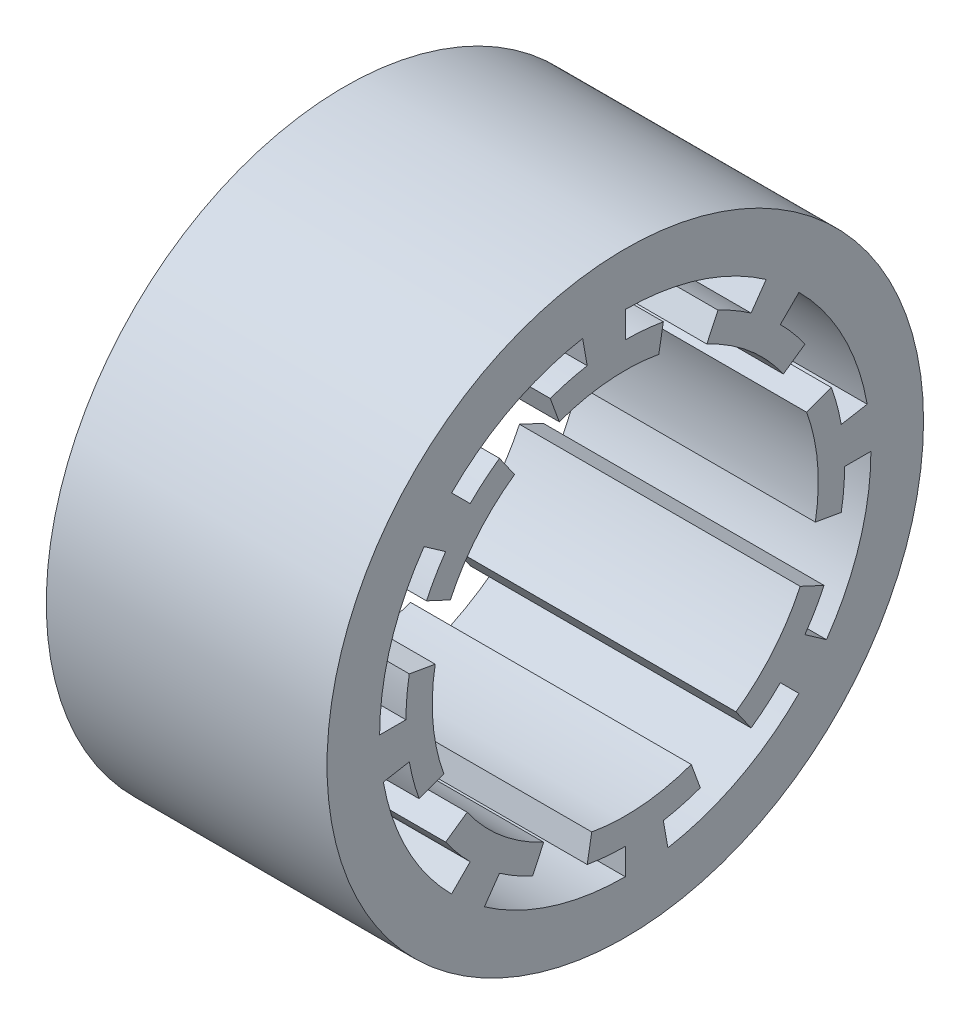
SolidWorks part; units mm, degrees
material "TPU 95A"
ref_plane "Front Plane" through (0, 0, 0) normal (1, 0, 0) x (0, 1, 0)
ref_plane "Top Plane" through (0, 0, 0) normal (0, 0, 1) x (0, 1, 0)
ref_plane "Right Plane" through (0, 0, 0) normal (0, 1, 0) x (-1, 0, 0)
sketch "Sketch1" plane through (0, 0, 0) normal (1, 0, 0) x (0, 1, 0)
  circle A0 centre (0, 0) radius 21.59
  circle A1 centre (0, 0) radius 17.78
  dimension "D1" = 43.18
  dimension "D2" = 35.56
extrude "Boss-Extrude1" add sketch "Sketch1" along normal blind 20.32
sketch "Sketch3" plane through (0, 0, 0) normal (1, 0, 0) x (0, 1, 0)
  line L0 (0, 0) -> (0, 17.78) construction
  line L1 (0, 0) -> (-3.0875, 17.5099) construction
  line L2 (0, 0) -> (-8.2099, 15.7711) construction
  line L3 (0, 0) -> (5.3465, 16.9571) construction
  line L4 (-3.0875, 17.5099) -> (-2.7567, 15.6338)
  line L5 (0, 0) -> (-5.4296, 14.9176) construction
  line L6 (0, 0) -> (2.7567, 15.6338) construction
  line L7 (0, 17.78) -> (0, 15.875)
  line L8 (-5.4296, 14.9176) -> (-4.778, 13.1275)
  line L9 (2.7567, 15.6338) -> (2.4259, 13.7578)
  circle A0 centre (0, 0) radius 17.78 construction
  circle A1 centre (0, 0) radius 15.875 construction
  circle A3 centre (0, 0) radius 13.97 construction
  arc A4 (-2.7567, 15.6338) -> (-5.4296, 14.9176) centre (0, 0) ccw
  arc A5 (0, 15.875) -> (2.7567, 15.6338) centre (0, 0) cw
  arc A6 (-4.778, 13.1275) -> (2.4259, 13.7578) centre (0, 0) cw
  arc A7 (-3.0875, 17.5099) -> (0, 17.78) centre (0, 0) cw
  dimension "D6" = 35.56
  dimension "D7" = 31.75
  dimension "D8" = 27.94
  dimension "D1" = 10
  dimension "D2" = 17.5
  dimension "D3" = 17.5
  dimension "D4" = 10
  dimension "D5" = 10
extrude "Boss-Extrude2" add sketch "Sketch3" along normal up to surface (20.32 mm away) up to face at (20.32, 0, -21.59)
sketch "Sketch4" plane through (0, 0, 0) normal (0, 0, 1) x (0, 1, 0)
  line L0 (0, 0) -> (0, -7.3257) construction
  line L1 (21.59, 0) -> (-21.59, 0) construction
pattern_circular "CirPattern1" count 8 every 45 about axis through (0, 0, 0) along (1, 0, 0) of "Boss-Extrude2"
